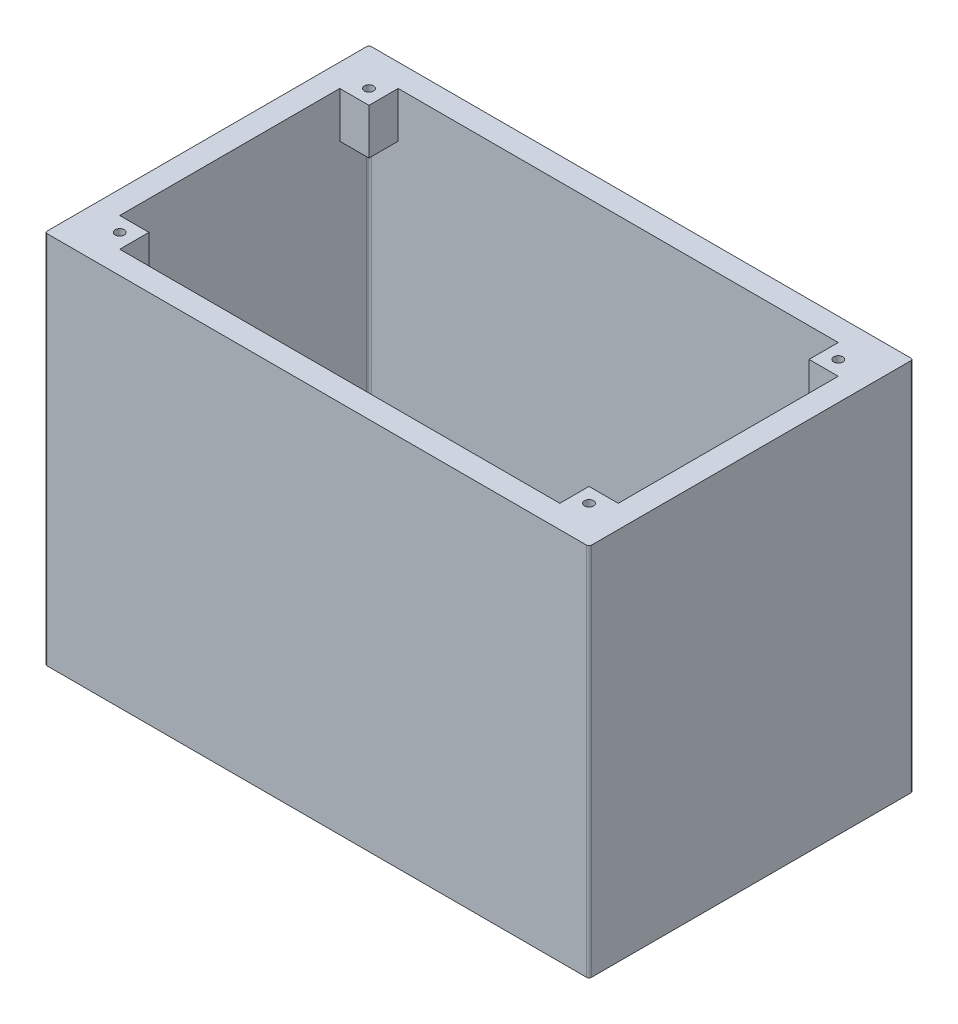
SolidWorks part; units mm, degrees
ref_plane "Front Plane" through (0, 0, 0) normal (0, 0, 1) x (1, 0, 0)
ref_plane "Top Plane" through (0, 0, 0) normal (0, 1, 0) x (1, 0, 0)
ref_plane "Right Plane" through (0, 0, 0) normal (1, 0, 0) x (0, 0, -1)
sketch "Sketch1" plane through (0, 0, 0) normal (0, 1, 0) x (1, 0, 0)
  line L1 (-29.8, -17.75) -> (29.8, -17.75)
  line L2 (-29.8, -17.75) -> (-29.8, 17.75)
  line L3 (-29.8, 17.75) -> (29.8, 17.75)
  line L4 (29.8, -17.75) -> (29.8, 17.75)
  line L5 (-29.8, -17.75) -> (29.8, 17.75) construction
  line L6 (-29.8, 17.75) -> (29.8, -17.75) construction
  point P0 (0, 0)
  dimension "D1" = 59.6
  dimension "D2" = 35.5
extrude "Boss-Extrude1" add sketch "Sketch1" along normal blind 2.5 contours L2 L1 L4 L3
sketch "Sketch3" plane through (0, 2.5, 0) normal (0, 1, 0) x (1, 0, 0)
  line L0 (-27.3, 15.25) -> (-27.3, -15.25)
  line L1 (-29.8, 17.75) -> (29.8, 17.75)
  line L2 (-29.8, 17.75) -> (-29.8, -17.75)
  line L3 (-29.8, -17.75) -> (29.8, -17.75)
  line L4 (29.8, 17.75) -> (29.8, -17.75)
  line L5 (-27.3, -15.25) -> (27.3, -15.25)
  line L6 (27.3, 15.25) -> (27.3, -15.25)
  line L7 (-27.3, 15.25) -> (27.3, 15.25)
  dimension "D1" = 2.5
extrude "Boss-Extrude4" add sketch "Sketch3" along normal blind 38.5
sketch "Sketch4" plane through (0, 41, 0) normal (0, 1, 0) x (1, 0, 0)
  line L0 (0, 0) -> (0, 15.25) construction
  line L1 (-27.3, 15.25) -> (-24.1, 15.25)
  line L2 (-27.3, 15.25) -> (-27.3, 12.05)
  line L3 (-27.3, 12.05) -> (-24.1, 12.05)
  line L4 (-24.1, 15.25) -> (-24.1, 12.05)
  line L5 (27.3, 15.25) -> (-27.3, 15.25) construction
  line L6 (0, 15.25) -> (0, 25.0147) construction
  line L7 (0, 0) -> (27.3, 0) construction
  line L8 (27.3, -15.25) -> (27.3, 15.25) construction
  line L9 (27.3, 0) -> (36.4444, 0) construction
  line L10 (-25.7, 15.25) -> (-25.7, 12.05)
  line L11 (27.3, 12.05) -> (24.1, 12.05)
  line L12 (24.1, 15.25) -> (24.1, 12.05)
  line L13 (27.3, 15.25) -> (24.1, 15.25)
  line L14 (27.3, 15.25) -> (27.3, 12.05)
  line L15 (27.3, -15.25) -> (27.3, -12.05)
  line L16 (27.3, -15.25) -> (24.1, -15.25)
  line L17 (24.1, -15.25) -> (24.1, -12.05)
  line L18 (27.3, -12.05) -> (24.1, -12.05)
  line L19 (-27.3, -15.25) -> (-24.1, -15.25)
  line L20 (-24.1, -15.25) -> (-24.1, -12.05)
  line L21 (-27.3, -12.05) -> (-24.1, -12.05)
  line L22 (-27.3, -15.25) -> (-27.3, -12.05)
  circle A0 centre (-25.7, 13.65) radius 0.5
  circle A1 centre (25.7, 13.65) radius 0.5
  circle A2 centre (25.7, -13.65) radius 0.5
  circle A3 centre (-25.7, -13.65) radius 0.5
  dimension "D3" = 1
  dimension "D1" = 3.2
  dimension "D2" = 3.2
extrude "Boss-Extrude7" add sketch "Sketch4" against normal blind 5
fillet "Fillet1" radius 0.25 4 edges at (29.8, 20.5, -17.75) (29.8, 20.5, 17.75) (-29.8, 20.5, -17.75) (-29.8, 20.5, 17.75)
fillet "Fillet2" radius 0.25 5 edges at (27.3, 19.25, 15.25) (-27.3, 19.25, 15.25) (27.3, 19.25, -15.25) (0, 2.5, -15.25) (-27.3, 19.25, -15.25)
sketch "Sketch6" plane through (-29.8, 0, 0) normal (-1, 0, 0) x (0, 0, 1)
  line L1 (17.5, 0) -> (5.5, 0)
  line L2 (17.5, 0) -> (17.5, 12) construction
  line L3 (17.5, 12) -> (5.5, 12) construction
  line L4 (5.5, 0) -> (5.5, 12) construction
  circle A0 centre (5.5, 12) radius 2
  dimension "D3" = 4
  dimension "D1" = 12
  dimension "D2" = 12
extrude "Cut-Extrude1" cut sketch "Sketch6" against normal blind 5 contours A0
fillet "Fillet4" radius 0.3 1 edges at (-29.8, 12, 7.5)
